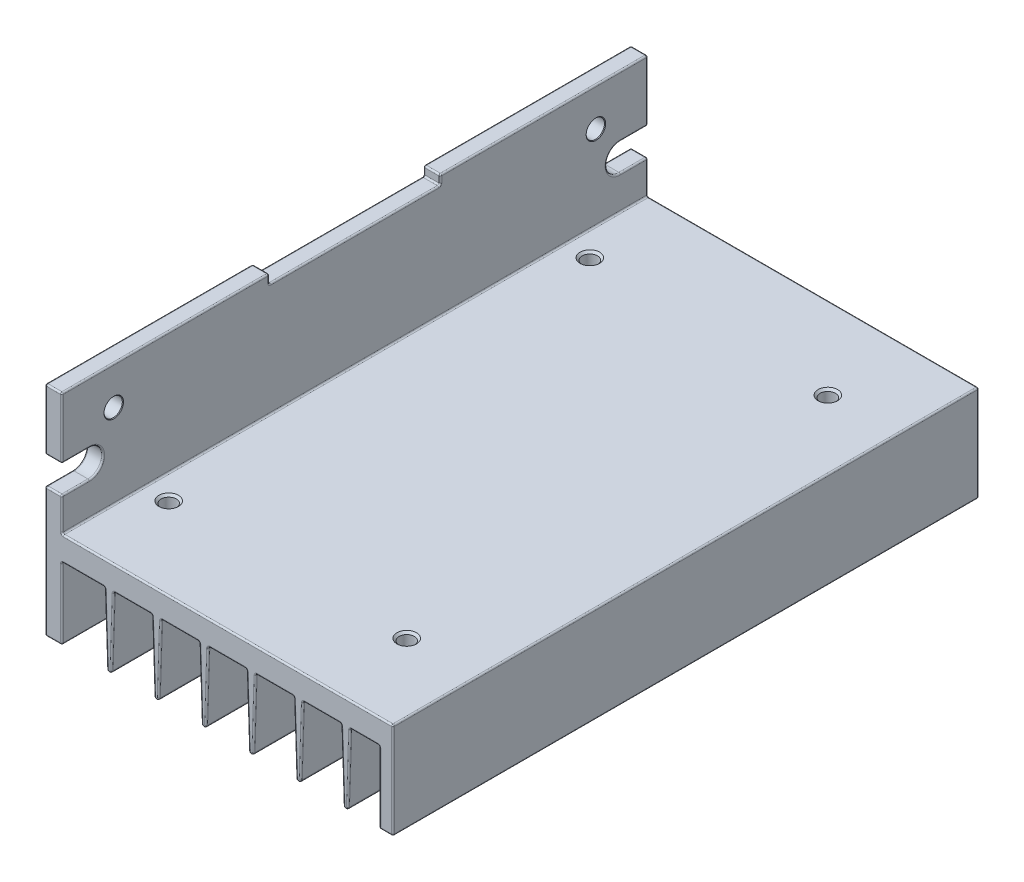
SolidWorks part; units mm, degrees
material "AlMgSi0.5-T4 (6060)"
ref_plane "Front Plane" through (0, 0, 0) normal (0, 0, 1) x (1, 0, 0)
ref_plane "Top Plane" through (0, 0, 0) normal (0, 1, 0) x (1, 0, 0)
ref_plane "Right Plane" through (0, 0, 0) normal (1, 0, 0) x (0, 0, -1)
sketch "Body Profile Sketch" plane through (0, 0, 0) normal (0, 0, 1) x (1, 0, 0)
  line L43 (0.25, 0) -> (54, 0)
  line L44 (54.25, -0.25) -> (54.25, -15.5)
  line L50 (54, -15.75) -> (52.25, -15.75)
  line L51 (52, -15.5) -> (52, -4.25)
  line L52 (51.75, -4) -> (47.4919, -4)
  line L53 (0, -4.25) -> (0, -15.5)
  line L54 (-0.25, -15.75) -> (-2.5, -15.75)
  line L55 (-2.75, -15.5) -> (-2.75, 19.75)
  line L56 (-2.5, 20) -> (-0.25, 20)
  line L57 (0, 19.75) -> (0, 0.25)
  line L58 (8.492, -4.2418) -> (8.1248, -15.3873)
  line L59 (7.008, -4.2418) -> (7.3752, -15.3873)
  line L60 (7.75, -4) -> (7.75, -15.75) construction
  line L61 (6.7581, -4) -> (0.25, -4)
  line L62 (8.5, -4) -> (7, -4) construction
  line L63 (16.242, -4.2418) -> (15.8748, -15.3873)
  line L64 (16.25, -4) -> (14.75, -4) construction
  line L65 (15.5, -4) -> (15.5, -15.75) construction
  line L66 (14.758, -4.2418) -> (15.1252, -15.3873)
  line L67 (23.992, -4.2418) -> (23.6248, -15.3873)
  line L68 (24, -4) -> (22.5, -4) construction
  line L69 (23.25, -4) -> (23.25, -15.75) construction
  line L70 (22.508, -4.2418) -> (22.8752, -15.3873)
  line L71 (31.742, -4.2418) -> (31.3748, -15.3873)
  line L72 (31.75, -4) -> (30.25, -4) construction
  line L73 (31, -4) -> (31, -15.75) construction
  line L74 (30.258, -4.2418) -> (30.6252, -15.3873)
  line L75 (39.492, -4.2418) -> (39.1248, -15.3873)
  line L76 (39.5, -4) -> (38, -4) construction
  line L77 (38.75, -4) -> (38.75, -15.75) construction
  line L78 (38.008, -4.2418) -> (38.3752, -15.3873)
  line L79 (47.242, -4.2418) -> (46.8748, -15.3873)
  line L80 (47.25, -4) -> (45.75, -4) construction
  line L81 (46.5, -4) -> (46.5, -15.75) construction
  line L82 (45.758, -4.2418) -> (46.1252, -15.3873)
  line L83 (14.5081, -4) -> (8.7419, -4)
  line L84 (22.2581, -4) -> (16.4919, -4)
  line L85 (30.0081, -4) -> (24.2419, -4)
  line L86 (37.7581, -4) -> (31.9919, -4)
  line L87 (45.5081, -4) -> (39.7419, -4)
  arc A28 (7.3752, -15.3873) -> (8.1248, -15.3873) centre (7.75, -15.375) ccw
  arc A29 (-0.25, 20) -> (0, 19.75) centre (-0.25, 19.75) cw
  arc A30 (-2.75, 19.75) -> (-2.5, 20) centre (-2.5, 19.75) cw
  arc A31 (0.25, 0) -> (0, 0.25) centre (0.25, 0.25) cw
  arc A32 (-2.5, -15.75) -> (-2.75, -15.5) centre (-2.5, -15.5) cw
  arc A33 (0, -15.5) -> (-0.25, -15.75) centre (-0.25, -15.5) cw
  arc A34 (0.25, -4) -> (0, -4.25) centre (0.25, -4.25) ccw
  arc A35 (7.008, -4.2418) -> (6.7581, -4) centre (6.7581, -4.25) ccw
  arc A36 (8.492, -4.2418) -> (8.7419, -4) centre (8.7419, -4.25) cw
  arc A37 (54, 0) -> (54.25, -0.25) centre (54, -0.25) cw
  arc A38 (52, -4.25) -> (51.75, -4) centre (51.75, -4.25) ccw
  arc A39 (54.25, -15.5) -> (54, -15.75) centre (54, -15.5) cw
  arc A40 (52.25, -15.75) -> (52, -15.5) centre (52.25, -15.5) cw
  arc A41 (16.242, -4.2418) -> (16.4919, -4) centre (16.4919, -4.25) cw
  arc A42 (15.1252, -15.3873) -> (15.8748, -15.3873) centre (15.5, -15.375) ccw
  arc A43 (14.758, -4.2418) -> (14.5081, -4) centre (14.5081, -4.25) ccw
  arc A44 (23.992, -4.2418) -> (24.2419, -4) centre (24.2419, -4.25) cw
  arc A45 (22.8752, -15.3873) -> (23.6248, -15.3873) centre (23.25, -15.375) ccw
  arc A46 (22.508, -4.2418) -> (22.2581, -4) centre (22.2581, -4.25) ccw
  arc A47 (31.742, -4.2418) -> (31.9919, -4) centre (31.9919, -4.25) cw
  arc A48 (30.6252, -15.3873) -> (31.3748, -15.3873) centre (31, -15.375) ccw
  arc A49 (30.258, -4.2418) -> (30.0081, -4) centre (30.0081, -4.25) ccw
  arc A50 (39.492, -4.2418) -> (39.7419, -4) centre (39.7419, -4.25) cw
  arc A51 (38.3752, -15.3873) -> (39.1248, -15.3873) centre (38.75, -15.375) ccw
  arc A52 (38.008, -4.2418) -> (37.7581, -4) centre (37.7581, -4.25) ccw
  arc A53 (47.242, -4.2418) -> (47.4919, -4) centre (47.4919, -4.25) cw
  arc A54 (46.1252, -15.3873) -> (46.8748, -15.3873) centre (46.5, -15.375) ccw
  arc A55 (45.758, -4.2418) -> (45.5081, -4) centre (45.5081, -4.25) ccw
  point P11 (7.75, -4)
  point P22 (-2.75, 20)
  point P25 (0, 0)
  point P28 (-2.75, -15.75)
  point P31 (0, -15.75)
  point P34 (0, -4)
  point P47 (54.25, -15.75)
  point P50 (52, -15.75)
  dimension "D7" = 0.375
  dimension "D8" = 1.5
  dimension "D10" = 0.25
  dimension "D11" = 6
  dimension "D1" = 57
  dimension "D2" = 2.25
  dimension "D3" = 4
  dimension "D4" = 2.75
  dimension "D5" = 11.75
  dimension "D6" = 35.75
  dimension "D9" = 7.75
  dimension "D12" = 7.75
extrude "Body" add sketch "Body Profile Sketch" along normal mid plane 96
sketch "Top Cut Out Sketch" plane through (0, 20, 0) normal (0, 1, 0) x (1, 0, 0)
  line L1 (14, -14) -> (-14, -14)
  line L2 (14, -14) -> (14, 14)
  line L3 (14, 14) -> (-14, 14)
  line L4 (-14, -14) -> (-14, 14)
  line L5 (14, -14) -> (-14, 14) construction
  line L6 (14, 14) -> (-14, -14) construction
  point P0 (0, 0)
  dimension "D1" = 28
extrude "Top Cut Out" cut sketch "Top Cut Out Sketch" against normal blind 1.5
sketch "Side Cut Out Sketch" plane through (0, 0, 0) normal (1, 0, 0) x (0, 0, -1)
  line L0 (48, 10) -> (43.5, 10)
  line L1 (48, 5.5) -> (43.5, 5.5)
  line L2 (48, 0.25) -> (48, 19.75) construction
  line L3 (0, 0) -> (0, 23.773) construction
  line L4 (-48, 10) -> (-43.5, 10)
  line L5 (-48, 5.5) -> (-43.5, 5.5)
  line L7 (48, 5.5) -> (48, 10)
  line L8 (-48, 5.5) -> (-48, 10)
  arc A0 (43.5, 10) -> (43.5, 5.5) centre (43.5, 7.75) ccw
  arc A1 (-43.5, 10) -> (-43.5, 5.5) centre (-43.5, 7.75) cw
  dimension "D1" = 87
  dimension "D3" = 2.25
  dimension "D2" = 7.75
extrude "Side Cut Out" cut sketch "Side Cut Out Sketch" against normal through all
hole_wizard "M3 Top Holes" positions "Sketch3" profile "Sketch4" tap size "M3" standard "ISO" end condition through all
sketch "Sketch3" plane through (0, 0, 0) normal (0, 1, 0) x (1, 0, 0)
  line L0 (43, 34.5) -> (4, -34.5) construction
  line L4 (0, -48) -> (0, 48) construction
  point P0 (43, 34.5)
  point P2 (43, -34.5)
  point P4 (4, -34.5)
  point P6 (4, 34.5)
  point P13 (23.5, 0)
  dimension "D1" = 69
  dimension "D2" = 39
  dimension "D3" = 43
sketch "Sketch4" plane through (43, 0, -34.5) normal (1, 0, 0) x (0, 0, 1)
  line L0 (0, 0) -> (0, 4)
  line L1 (0, 4) -> (1.6, 4)
  line L2 (1.25, 3.65) -> (1.25, 0.35)
  line L3 (1.25, 0.35) -> (1.6, 0)
  line L5 (1.6, 0) -> (0, 0)
  line L6 (-1.25, 0.35) -> (-1.6, 0) construction
  line L7 (1.6, 4) -> (1.25, 3.65)
  line L8 (-1.6, 4) -> (-1.25, 3.65) construction
  line L11 (0, -6.35) -> (0, 107.95) construction
  dimension "Thru Tap Drill Dia." = 2.5
  dimension "Thru Tap Drill Depth" = 4
  dimension "Near C'Sink Dia." = 3.2
  dimension "Near C'Sink Angle" = 90
  dimension "Far C'Sink Dia." = 3.2
  dimension "Far C'Sink Angle" = 90
cosmetic thread "Hole Thread1" parameters "D2"=3
cosmetic thread "Hole Thread2" parameters "D2"=3
cosmetic thread "Hole Thread3" parameters "D2"=3
cosmetic thread "Hole Thread4" parameters "D2"=3
hole_wizard "Ø3.0 Side Holes" positions "Sketch5" profile "Sketch6" hole size "Ø3.0" standard "ISO" end condition through all
sketch "Sketch5" plane through (0, 0, 0) normal (1, 0, 0) x (0, 0, -1)
  line L0 (-39.5, 13.75) -> (39.5, 13.75) construction
  point P0 (39.5, 13.75)
  point P2 (-39.5, 13.75)
  point P9 (0, 13.75)
  dimension "D1" = 79
  dimension "D2" = 13.75
sketch "Sketch6" plane through (0, 13.75, -39.5) normal (0, 1, 0) x (0, 0, -1)
  line L0 (0, 0) -> (0, 2.75)
  line L1 (0, 2.75) -> (1.6, 2.75)
  line L2 (1.5, 2.65) -> (1.5, 0.1)
  line L3 (1.5, 0.1) -> (1.6, 0)
  line L5 (1.6, 0) -> (0, 0)
  line L6 (-1.5, 0.1) -> (-1.6, 0) construction
  line L7 (1.6, 2.75) -> (1.5, 2.65)
  line L8 (-1.6, 2.75) -> (-1.5, 2.65) construction
  line L11 (0, -6.35) -> (0, 107.95) construction
  dimension "Thru Hole Dia." = 3
  dimension "Thru Hole Depth" = 2.75
  dimension "Near C'Sink Dia." = 3.2
  dimension "Near C'Sink Angle" = 90
  dimension "Far C'Sink Dia." = 3.2
  dimension "Far C'Sink Angle" = 90
fillet "Production Fillet" radius 0.25 124 edges at (-1.375, 20, -14) (-1.375, 20, 14) (-0.0732, 19.9268, -14) (-2.6768, 19.9268, -14) (-2.6768, 19.9268, 14) (0, 19.125, -14) (-2.75, 19.125, 14) (-2.75, 10, -45.75) (-2.75, 7.75, -41.25) (0, 10, -45.75) (0, 7.75, -41.25) (-2.75, 10, 45.75) (-2.75, 7.75, 41.25) (0, 7.75, 41.25) (0, 2.875, 48) (0.0732, 0.0732, 48) (27.125, 0, 48) (54.1768, -0.0732, 48) (54.25, -7.875, 48) (54.1768, -15.6768, 48) (52.0732, -15.6768, 48) (52, -9.875, 48) (51.9268, -4.0732, 48) (49.6209, -4, 48) (47.3181, -4.0703, 48) (47.0584, -9.8146, 48) (45.9416, -9.8146, 48) (45.6819, -4.0703, 48) (42.625, -4, 48) (39.5681, -4.0703, 48) (39.3084, -9.8146, 48) (38.75, -15.75, 48) (38.1916, -9.8146, 48) (37.9319, -4.0703, 48) (34.875, -4, 48) (31.8181, -4.0703, 48) (31.5584, -9.8146, 48) (31, -15.75, 48) (30.4416, -9.8146, 48) (30.1819, -4.0703, 48) (24.0681, -4.0703, 48) (23.8084, -9.8146, 48) (22.4319, -4.0703, 48) (19.375, -4, 48) (16.3181, -4.0703, 48) (16.0584, -9.8146, 48) (15.5, -15.75, 48) (14.9416, -9.8146, 48) (8.5681, -4.0703, 48) (0.0732, -4.0732, 48) (0, -9.875, 48) (-0.0732, -15.6768, 48) (-1.375, -15.75, 48) (-2.6768, -15.6768, 48) (-2.75, -5, -48) (-2.6768, -15.6768, -48) (-1.375, -15.75, -48) (-0.0732, -15.6768, -48) (0, -9.875, -48) (0.0732, -4.0732, -48) (3.5041, -4, -48) (6.9319, -4.0703, -48) (7.1916, -9.8146, -48) (7.75, -15.75, -48) (8.3084, -9.8146, -48) (8.5681, -4.0703, -48) (11.625, -4, -48) (14.6819, -4.0703, -48) (14.9416, -9.8146, -48) (15.5, -15.75, -48) (16.0584, -9.8146, -48) (16.3181, -4.0703, -48) (19.375, -4, -48) (22.4319, -4.0703, -48) (22.6916, -9.8146, -48) (23.25, -15.75, -48) (24.0681, -4.0703, -48) (27.125, -4, -48) (30.1819, -4.0703, -48) (30.4416, -9.8146, -48) (31, -15.75, -48) (31.8181, -4.0703, -48) (34.875, -4, -48) (37.9319, -4.0703, -48) (38.1916, -9.8146, -48) (39.3084, -9.8146, -48) (39.5681, -4.0703, -48) (45.6819, -4.0703, -48) (45.9416, -9.8146, -48) (46.5, -15.75, -48) (47.3181, -4.0703, -48) (49.6209, -4, -48) (51.9268, -4.0732, -48) (52, -9.875, -48) (52.0732, -15.6768, -48) (53.125, -15.75, -48) (54.1768, -15.6768, -48) (54.25, -7.875, -48) (54.1768, -0.0732, -48) (27.125, 0, -48) (0.0732, 0.0732, -48) (0, 2.875, -48) (-2.75, 5.5, -45.75) (-1.375, 5.5, -48) (0, 5.5, -45.75) (0, 14.875, -48) (-0.0732, 19.9268, -48) (-1.375, 20, -48) (-2.6768, 19.9268, -48) (-2.75, 14.875, -48) (-1.375, 10, -48) (-1.375, 5.5, 48) (-2.75, 5.5, 45.75) (0, 5.5, 45.75) (-2.6768, 19.9268, 48) (-1.375, 20, 48) (-0.0732, 19.9268, 48) (0, 14.875, 48) (-1.375, 10, 48) (-2.75, 14.875, 48) (-1.375, 18.5, -14) (0, 18.5, 0) (-1.375, 18.5, 14) (-2.75, -5, 48)
